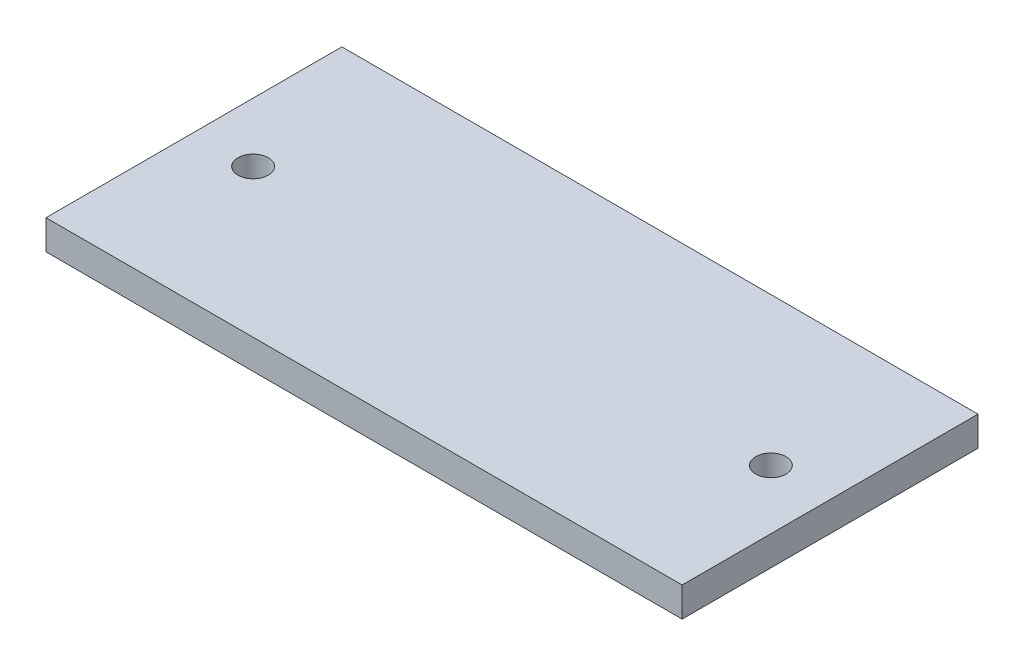
SolidWorks part; units mm, degrees
ref_plane "Front Plane" through (0, 0, 0) normal (0, 0, 1) x (1, 0, 0)
ref_plane "Top Plane" through (0, 0, 0) normal (0, 1, 0) x (1, 0, 0)
ref_plane "Right Plane" through (0, 0, 0) normal (1, 0, 0) x (0, 0, -1)
sketch "Sketch1" plane through (0, 0, 0) normal (0, 1, 0) x (1, 0, 0)
  line L0 (-17.5, 0) -> (17.5, 0) construction
  line L2 (-21.5, 10) -> (21.5, 10)
  line L3 (-21.5, 10) -> (-21.5, -10)
  line L4 (-21.5, -10) -> (21.5, -10)
  line L5 (21.5, 10) -> (21.5, -10)
  line L6 (-21.5, 10) -> (21.5, -10) construction
  line L7 (-21.5, -10) -> (21.5, 10) construction
  circle A0 centre (-17.5, 0) radius 1.025
  circle A1 centre (17.5, 0) radius 1.025
  point P3 (0, 0)
  point P4 (0, 0)
  dimension "D4" = 2.05
  dimension "D1" = 35
  dimension "D2" = 20
  dimension "D3" = 43
extrude "Boss-Extrude1" add sketch "Sketch1" along normal blind 2
